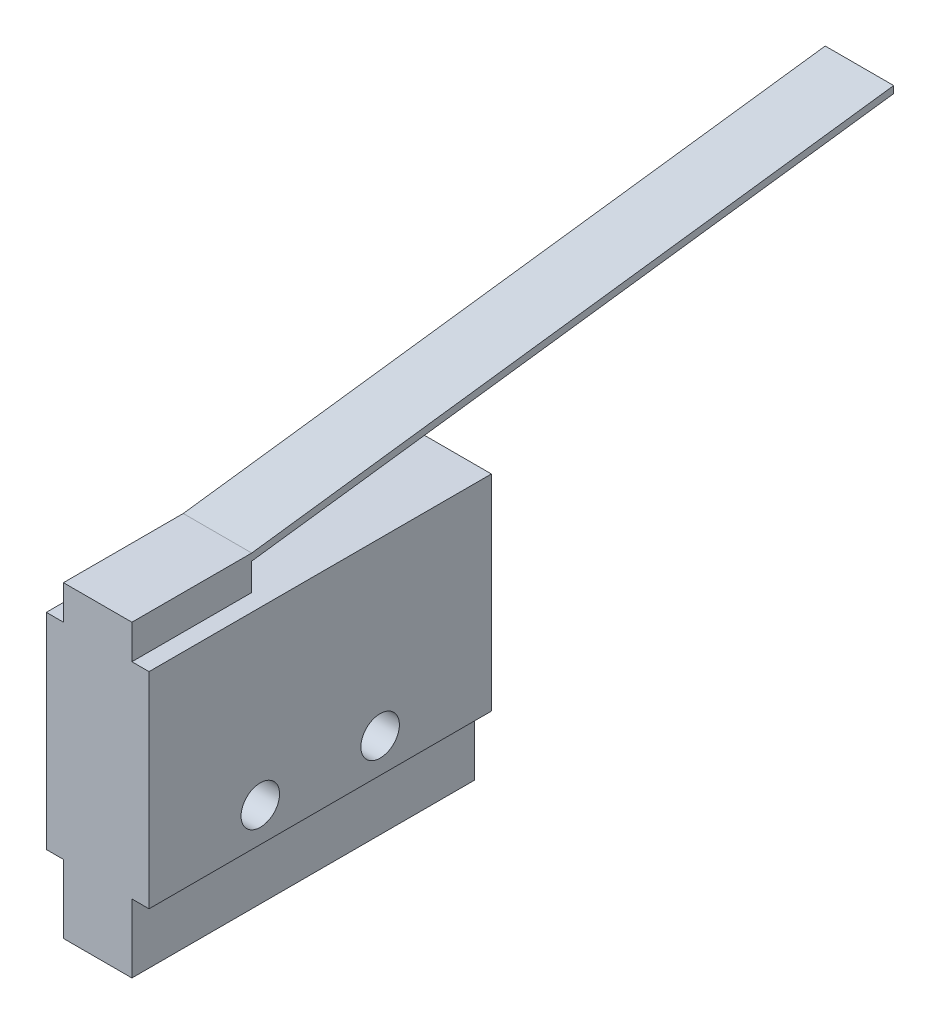
SolidWorks part; units mm, degrees
ref_plane "Front Plane" through (0, 0, 0) normal (0, 0, 1) x (1, 0, 0)
ref_plane "Top Plane" through (0, 0, 0) normal (0, 1, 0) x (1, 0, 0)
ref_plane "Right Plane" through (0, 0, 0) normal (1, 0, 0) x (0, 0, -1)
sketch "Sketch1" plane through (0, 0, 0) normal (0, 1, 0) x (1, 0, 0)
  line L1 (0, 0) -> (6, 0)
  line L2 (0, 0) -> (0, 20)
  line L3 (0, 20) -> (6, 20)
  line L4 (6, 0) -> (6, 20)
  dimension "D1" = 20
  dimension "D2" = 6
extrude "Boss-Extrude1" add sketch "Sketch1" along normal blind 10
sketch "Sketch2" plane through (6, 0, 0) normal (1, 0, 0) x (0, 0, -1)
  line L0 (0, 0) -> (20, 0) construction
  circle A0 centre (6.5, 0) radius 1.125
  circle A1 centre (13.5, 0) radius 1.125
  dimension "D1" = 2.25
  dimension "D2" = 2.25
  dimension "D3" = 7
  dimension "D4" = 6.5
sketch "Sketch3" plane through (0, 0, 0) normal (0, -1, 0) x (-1, 0, 0)
  line L1 (0, 0) -> (-6, 0)
  line L2 (0, 0) -> (0, 20)
  line L3 (0, 20) -> (-6, 20)
  line L4 (-6, 0) -> (-6, 20)
extrude "Boss-Extrude2" add sketch "Sketch3" along normal blind 2
extrude "Cut-Extrude1" cut sketch "Sketch2" against normal blind 7
sketch "Sketch4" plane through (0, -2, 0) normal (0, -1, 0) x (-1, 0, 0)
  line L0 (-6, 20) -> (-6, 0) construction
  line L1 (-5, 20) -> (-1, 20)
  line L2 (-5, 20) -> (-5, 0)
  line L3 (-5, 0) -> (-1, 0)
  line L4 (-1, 20) -> (-1, 0)
  line L5 (0, 20) -> (-6, 20) construction
  dimension "D1" = 4
  dimension "D2" = 1
  dimension "D3" = 20
  dimension "D4" = 0
extrude "Boss-Extrude3" add sketch "Sketch4" along normal blind 4
sketch "Sketch5" plane through (0, 10, 0) normal (0, 1, 0) x (1, 0, 0)
  line L0 (0, 0) -> (6, 0) construction
  line L1 (1, 0) -> (5, 0)
  line L2 (1, 0) -> (1, 7)
  line L3 (1, 7) -> (5, 7)
  line L4 (5, 0) -> (5, 7)
  line L5 (0, 20) -> (0, 0) construction
  dimension "D1" = 4
  dimension "D2" = 1
  dimension "D3" = 7
extrude "Boss-Extrude4" add sketch "Sketch5" along normal blind 2
sketch "Sketch7" plane through (5, 0, 0) normal (1, 0, 0) x (0, 0, -1)
  line L0 (7, 12) -> (44.5, 16.9)
  line L1 (44.5, 16.9) -> (44.5, 16.4912)
  line L2 (44.5, 16.4912) -> (7, 11.5912)
  line L3 (7, 12) -> (7, 10) construction
  line L8 (0, 10) -> (7, 10)
  line L9 (7, 10) -> (7, 12)
  line L10 (7, 12) -> (0, 12)
  line L11 (0, 12) -> (0, 10)
  line L12 (0, 10) -> (7, 10)
  line L13 (7, 10) -> (7, 11.5912)
  line L14 (7, 12) -> (0, 12)
  line L15 (0, 12) -> (0, 10)
  dimension "D1" = 4.9
  dimension "D2" = 37.5
  dimension "D3" = 0.4088
  dimension "D4" = 0
extrude "Boss-Extrude5" add sketch "Sketch7" against normal blind 4
